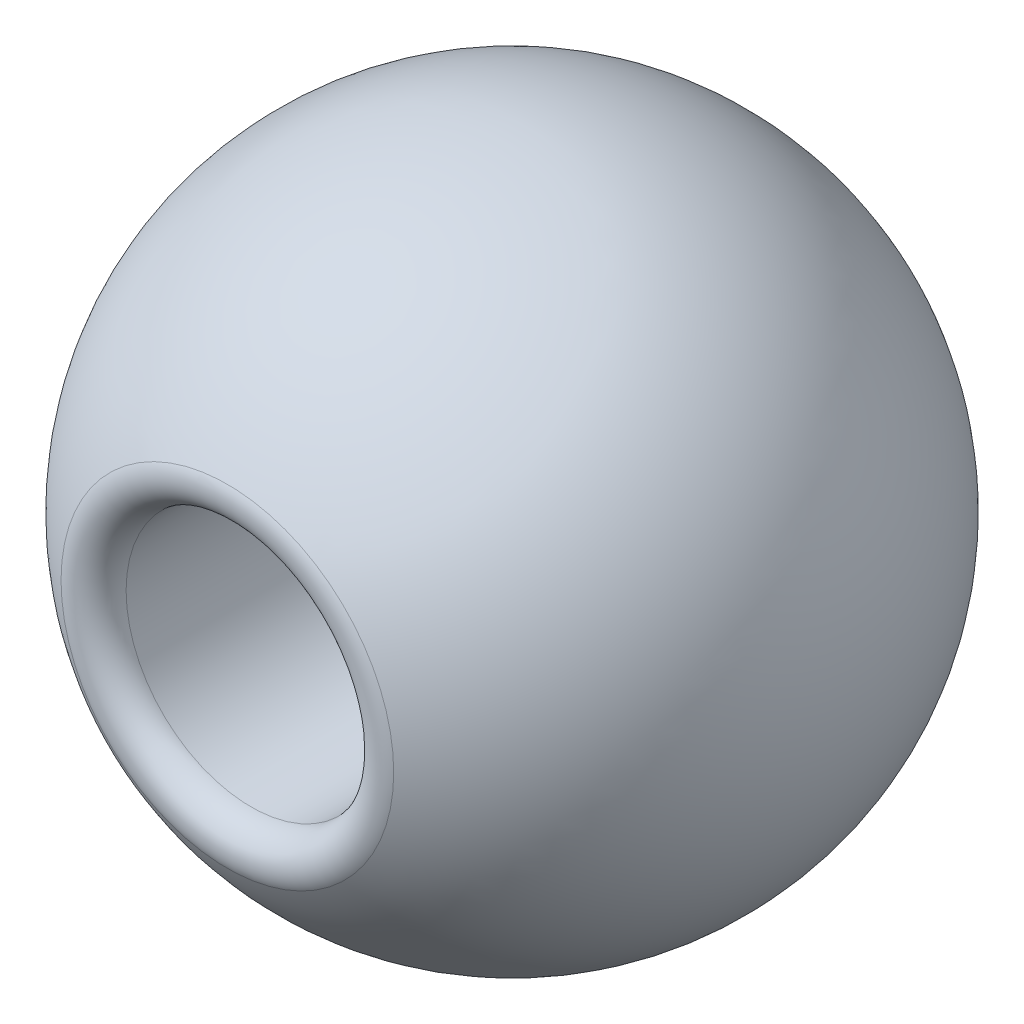
SolidWorks part; units mm, degrees
ref_plane "정면" through (0, 0, 0) normal (0, 0, 1) x (1, 0, 0)
ref_plane "윗면" through (0, 0, 0) normal (0, 1, 0) x (1, 0, 0)
ref_plane "우측면" through (0, 0, 0) normal (1, 0, 0) x (0, 0, -1)
sketch "스케치1" plane through (0, 0, 0) normal (0, 0, 1) x (1, 0, 0)
  line L0 (0, 11.7897) -> (0, -13.2661) construction
  line L1 (0, 12) -> (0, -12)
  arc A0 (0, 12) -> (0, -12) centre (0, 0) ccw
  dimension "D1" = 24
revolve "회전2" add sketch "스케치1" angle 360 about L0
sketch "스케치2" plane through (0, 0, 0) normal (0, 0, 1) x (1, 0, 0)
  circle A1 centre (0, 0) radius 4.55
  dimension "D1" = 9.1
extrude "컷-돌출1" cut sketch "스케치2" against normal mid plane 30 contours A1
fillet "필렛1" radius 1 2 edges at (-4.55, 0, 11.1039) (4.55, 0, -11.1039)
ref_point "점1"
